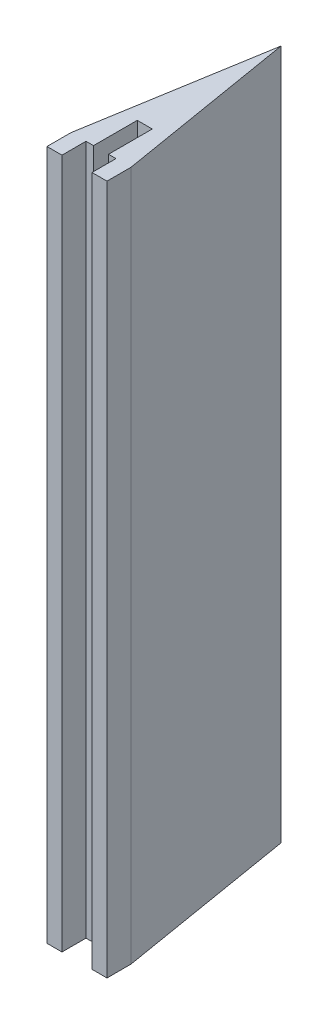
SolidWorks part; units mm, degrees
material "6061-T6 (SS)"
ref_plane "Front Plane" through (0, 0, 0) normal (0, 0, 1) x (1, 0, 0)
ref_plane "Top Plane" through (0, 0, 0) normal (0, 1, 0) x (1, 0, 0)
ref_plane "Right Plane" through (0, 0, 0) normal (1, 0, 0) x (0, 0, -1)
sketch "Sketch1" plane through (0, 0, 0) normal (0, 1, 0) x (1, 0, 0)
  line L0 (0, 0) -> (0, 38.1) construction
  line L1 (0, 38.1) -> (-6.35, 0)
  line L2 (0, 38.1) -> (6.35, 0)
  line L3 (0, 18.7872) -> (3.2182, -0.522) construction
  line L4 (0, 18.7872) -> (-3.2182, -0.522) construction
  line L5 (0, 0) -> (3.175, 0) construction
  line L6 (0, 0) -> (-3.175, 0) construction
  line L7 (-3.175, 0) -> (-3.175, -5.08)
  line L8 (-3.175, -5.08) -> (-6.35, -5.08)
  line L9 (-6.35, -5.08) -> (-6.35, 0)
  line L10 (3.175, 0) -> (3.175, -5.08)
  line L11 (3.175, -5.08) -> (6.35, -5.08)
  line L12 (6.35, -5.08) -> (6.35, 0)
  line L13 (-3.175, 0) -> (-1.5875, 0)
  line L14 (-1.5875, 0) -> (-1.5875, 9.2622)
  line L15 (-1.5875, 9.2622) -> (1.5875, 9.2622)
  line L16 (1.5875, 9.2622) -> (1.5875, 0)
  line L17 (1.5875, 0) -> (3.175, 0)
  dimension "D7" = 1.5875
  dimension "D1" = 38.1
  dimension "D2" = 6.35
  dimension "D3" = 6.35
  dimension "D5" = 3.175
  dimension "D6" = 3.175
  dimension "D8" = 5.08
  dimension "D9" = 5.08
  dimension "D4" = 3.175
extrude "Boss-Extrude1" add sketch "Sketch1" along normal blind 146.05
